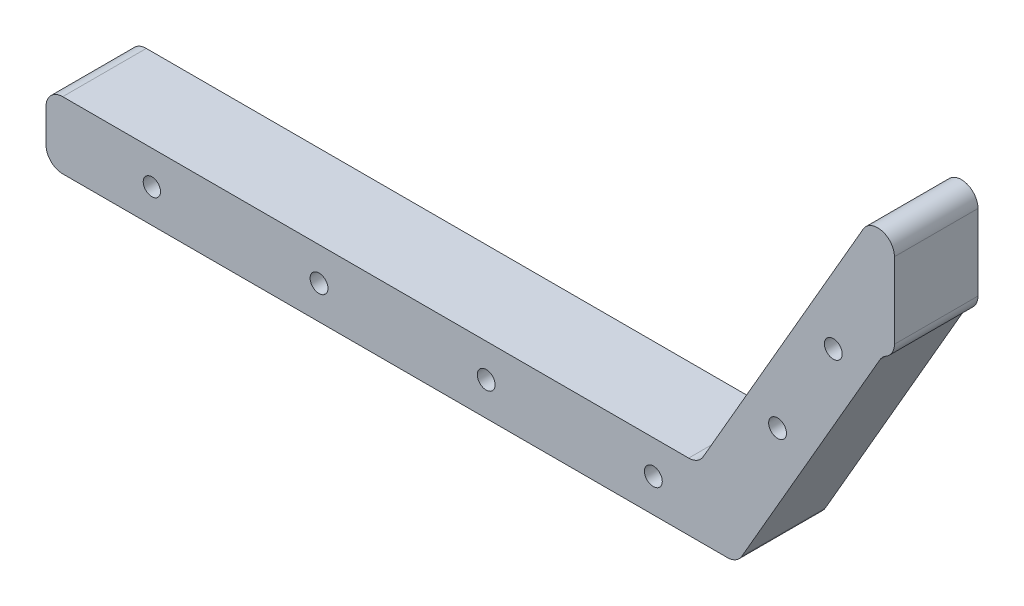
SolidWorks part; units mm, degrees
material "ABS"
ref_plane "前视基准面" through (0, 0, 0) normal (0, 0, 1) x (1, 0, 0)
ref_plane "上视基准面" through (0, 0, 0) normal (0, 1, 0) x (1, 0, 0)
ref_plane "右视基准面" through (0, 0, 0) normal (1, 0, 0) x (0, 0, -1)
other "Configuration Table"
sketch "草图2" plane through (0, 0, 0) normal (0, 0, 1) x (1, 0, 0)
  line B0 (110.2624, 45.9519) -> (110.2624, 72.9519)
  line B1 (0, 12) -> (0, 0)
  line B2 (0, 0) -> (80.2679, 0)
  line B3 (82.866, 1.5) -> (107.6643, 44.4519)
  line B4 (110.2624, 72.9519) -> (75.9378, 13.5)
  line B5 (73.3397, 12) -> (0, 12)
  circle B6 centre (99.2927, 41.9519) radius 1.6
  circle B7 centre (89.2927, 24.6314) radius 1.6
  circle B8 centre (67, 6) radius 1.6
  circle B9 centre (37, 6) radius 1.6
  arc B10 (80.2679, 0) -> (82.866, 1.5) centre (80.2679, 3) ccw
  arc B11 (110.2624, 45.9519) -> (107.6643, 44.4519) centre (110.2624, 42.9519) ccw
  arc B12 (73.3397, 12) -> (75.9378, 13.5) centre (73.3397, 15) ccw
  circle B13 centre (7, 6) radius 1.6
sketch_block_instance "块2-1"
sketch_block "块2"
extrude "凸台-拉伸1" add sketch "草图2" along normal blind 15
fillet "圆角1" radius 3 4 edges at (0, 0, 7.5) (0, 12, 7.5) (110.2624, 72.9519, 7.5) (110.2624, 45.9519, 7.5)
sketch "草图3" plane through (0, 0, 15) normal (0, 0, 1) x (1, 0, 0)
  line L0 (-42, 6) -> (3, 6) construction
  line L1 (3, 12) -> (-42, 12)
  line L2 (3, 12) -> (3, 0)
  line L3 (3, 0) -> (-42, 0)
  line L4 (-42, 12) -> (-42, 0)
  circle A0 centre (-23, 6) radius 1.55
  circle A1 centre (7, 6) radius 1.6 construction
  dimension "D3" = 3.1
  dimension "D4" = 30
  dimension "D1" = 45
  dimension "D2" = 12
extrude "凸台-拉伸2" add sketch "草图3" against normal blind 15
fillet "圆角2" radius 3 2 edges at (-42, 0, 7.5) (-42, 12, 7.5)
